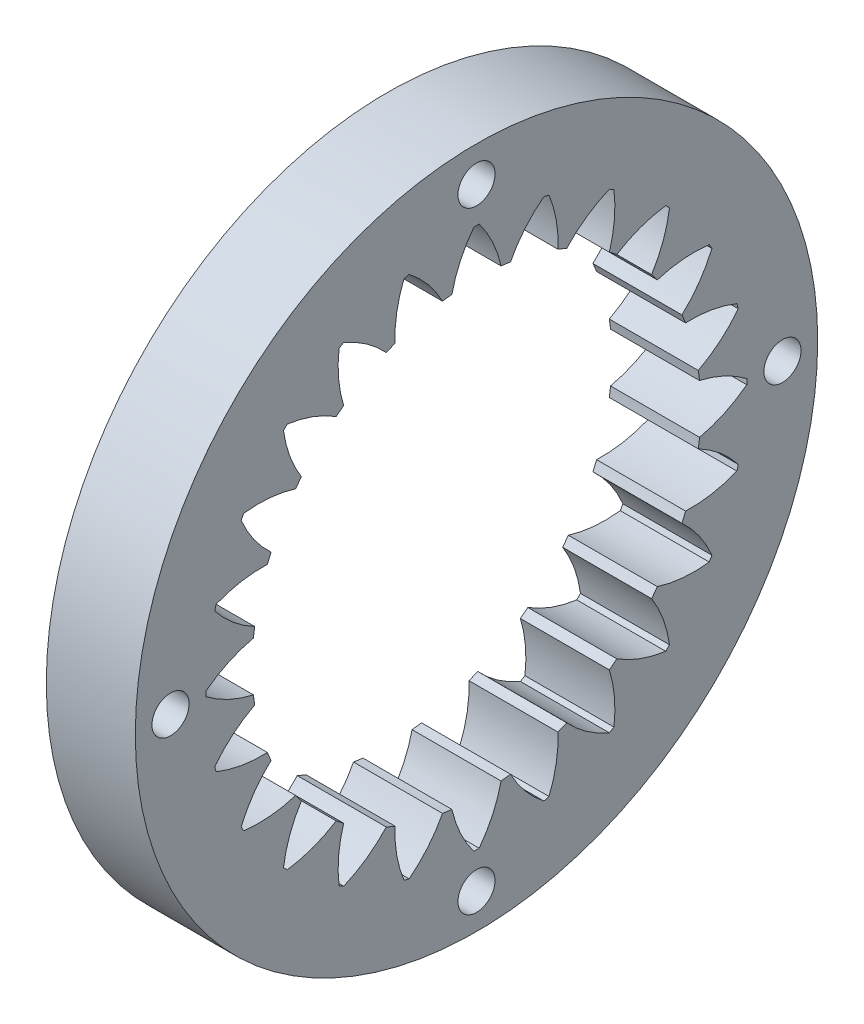
SolidWorks part; units mm, degrees
ref_plane "Plane1" through (0, 0, 0) normal (0, 0, 1) x (1, 0, 0)
ref_plane "Plane2" through (0, 0, 0) normal (0, 1, 0) x (1, 0, 0)
ref_plane "Plane3" through (0, 0, 0) normal (1, 0, 0) x (0, 0, -1)
sketch "HoldingSke" plane through (0, 0, 0) normal (0, 1, 0) x (1, 0, 0)
  line L0 (0, 0) -> (0.3322, -0.1479)
  line L1 (-15, 0) -> (100, 0) construction
  line L2 (0, 0) -> (-2.1039, 2.3779)
  line L3 (0, 0) -> (-11.863, 4.5341)
  line L4 (0, 0) -> (7.8894, 3.5126)
  line L5 (0, 0) -> (-23.7986, -8.8762)
  line L6 (0, 0) -> (-10.5278, -7.1032)
  line L7 (-2.1039, 2.3779) -> (3.3635, 27.1825)
  line L8 (-76.2, 5.1279) -> (-54.61, 5.1279)
  line L9 (-71.009, 38.7566) -> (-53.1078, 45.2721)
  line L10 (-76.2, 71.12) -> (104.1128, 71.12)
  line L11 (0, 0) -> (-12, 0)
  line L12 (-76.2, 101.6) -> (-76.103, 101.6)
  line L13 (24.9733, 27.94) -> (52.9518, 28.4284)
  line L14 (24.9733, 27.94) -> (24.9743, 27.94)
  line L15 (24.9733, 27.94) -> (100.4006, 29.5858)
  circle A0 centre (0, 0) radius 12.5
  circle A1 centre (0, 0) radius 12.7
  circle A2 centre (0, 0) radius 12.7
  dimension "MHD" = 25.4
  dimension "Hub_dia" = 25.4
  dimension "Diameter" = 25
  dimension "Num_teeth" = 24
  dimension "Pitch" = 0.3636
  dimension "Overall_len" = 25.4
  dimension "Show_teeth" = 24
  dimension "Thickness" = 12.7
  dimension "OAL" = 25.4001
  dimension "T_dim" = 21.59
  dimension "Ap" = 20
  dimension "H" = 19.05
  dimension "Pitch_radius" = 180.3128
  dimension "Width" = 12
  dimension "Backlash" = 0.097
  dimension "Addendum_fac" = 1
  dimension "Dedendum_fac" = 1.25
  dimension "Clearance_fac" = 0.25
  dimension "Dedendum_add" = 0.001
  dimension "Module" = 2.75
sketch "BasProSke" plane through (0, 0, 0) normal (0, 1, 0) x (1, 0, 0)
  line L0 (-10, 0) -> (60, 0) construction
  line L1 (0, 30.25) -> (0, 36.4639)
  line L2 (0, 30.25) -> (12, 30.25)
  line L3 (12, 30.25) -> (12, 36.4639)
  line L4 (12, 36.4639) -> (0, 36.4639)
  dimension "Thickness" = 12
  dimension "Diameter" = 72.9278
  dimension "Inside_diameter" = 60.5
revolve "Base-Revolve" add sketch "BasProSke" angle 360 about L0
sketch "TooCutSke" plane through (0, 0, 0) normal (1, 0, 0) x (0, 0, -1)
  line L3 (2.4008, 32.9126) -> (2.4008, 53.6633) construction
  line L4 (0, 0) -> (0, 59.563) construction
  line L5 (0, 0) -> (-8.9185, 67.7429) construction
  line L6 (-12.7878, 26.4661) -> (33.8762, 32.6096) construction
  circle A0 centre (0, 0) radius 33 construction
  circle A1 centre (0, 0) radius 36.4385 construction
  circle A2 centre (0, 0) radius 27.9089 construction
  circle A3 centre (0, 0) radius 30.2246 construction
  arc A4 (3.3201, 30.0417) -> (0.359, 36.4367) centre (-12.7878, 26.4661) ccw
  arc A5 (3.3201, 30.0417) -> (-3.3201, 30.0417) centre (0, 0) ccw
  arc A6 (0.359, 36.4367) -> (-0.359, 36.4367) centre (0, 0) ccw
  arc A7 (-0.359, 36.4367) -> (-3.3201, 30.0417) centre (12.7878, 26.4661) ccw
  dimension "Pitch_dia" = 66
  dimension "Base_dia" = 55.8177
  dimension "Root_dia" = 72.877
  dimension "Overcut_dia" = 60.4492
  dimension "Flank_rad" = 16.5
  dimension "Half_ang" = 7.5
  dimension "Half_CT" = 2.4008
extrude "ToothCut" cut sketch "TooCutSke" along normal through all
fillet "Breaks" [suppressed] radius 0.275
fillet "RootFillets" [suppressed] radius 0.6885
pattern_circular "TeethCuts" count 24 every 15 about axis through (-10, 0, 0) along (1, 0, 0) of "RootFillets", "Breaks", "ToothCut"
sketch "Sketch1" plane through (12, 0, 0) normal (1, 0, 0) x (0, 0, -1)
  circle A0 centre (0, 0) radius 36.4385
  circle A1 centre (0, 0) radius 46
  dimension "D1" = 72.877
  dimension "D2" = 92
extrude "Boss-Extrude1" add sketch "Sketch1" against normal blind 12
sketch "Sketch2" plane through (12, 0, 0) normal (1, 0, 0) x (0, 0, -1)
  circle A0 centre (41.25, 0) radius 2.5
  circle A1 centre (0, -41.25) radius 2.5
  circle A2 centre (-41.25, 0) radius 2.5
  circle A3 centre (0, 41.25) radius 2.5
  point P12 (0, 0)
  dimension "D1" = 5
  dimension "D2" = 41.25
  dimension "D3" = 4
extrude "Cut-Extrude1" cut sketch "Sketch2" against normal blind 12
equation "' \"Module@HoldingSke\" = 6.35"
equation "' \"Num_teeth@HoldingSke\" = 24"
equation "' \"Ap@HoldingSke\" =  14.5"
equation "' \"Ap@HoldingSke\" = 14.5"
equation "' \"Width@HoldingSke\" = 12"
equation "' \"Diameter@HoldingSke\" = 8 * 25.4"
equation "' \"Show_teeth@HoldingSke\" = 100"
equation "' \"Backlash@HoldingSke\" = 0.009 * 25.4"
equation "' \"Addendum_fac@HoldingSke\" = 1.0"
equation "' \"Dedendum_fac@HoldingSke\" = 1.25"
equation "' \"Dedendum_add@HoldingSke\" = 0.00005 * 25.4"
equation "' \"Clearance_fac@HoldingSke\" = 0.25"
equation "\"Pitch@HoldingSke\" = 1 / \"Module@HoldingSke\" "
equation "\"Overcut_dia@TooCutSke\" = (\"Num_teeth@HoldingSke\" - 2 * \"Addendum_fac@HoldingSke\") / \"Pitch@HoldingSke\" - 0.002 * 25.4"
equation "\"Pitch_dia@TooCutSke\" = \"Num_teeth@HoldingSke\" / \"Pitch@HoldingSke\""
equation "\"Base_dia@TooCutSke\" = \"Num_teeth@HoldingSke\" / \"Pitch@HoldingSke\" * cos((\"Ap@HoldingSke\"  * 3.14159265 / 180)) * 0.90"
equation "\"Root_dia@TooCutSke\" = \"Num_teeth@HoldingSke\"  / \"Pitch@HoldingSke\" + 2 *  \"Dedendum_fac@HoldingSke\"/ \"Pitch@HoldingSke\" + \"Dedendum_add@HoldingSke\" * 2"
equation "\"Half_ang@TooCutSke\" = 180 / \"Num_teeth@HoldingSke\""
equation "\"Half_CT@TooCutSke\" = \"Num_teeth@HoldingSke\" / \"Pitch@HoldingSke\" * sin((3.14159265 / 2 / \"Num_teeth@HoldingSke\")) / 2 + 10 * \"Backlash@HoldingSke\" / 4"
equation "\"Flank_rad@TooCutSke\" = \"Num_teeth@HoldingSke\" / \"Pitch@HoldingSke\" / 4"
equation "\"Radius@RootFillets\"= \"Clearance_fac@HoldingSke\" / \"Pitch@HoldingSke\" + \"Dedendum_add@HoldingSke\""
equation "\"Break_rad@Breaks\" = 0.02 / \"Pitch@HoldingSke\" * 5"
equation "\"Num_teeth@TeethCuts\" = int( \"Show_teeth@HoldingSke\" ) + 1"
equation "\"Num_teeth@TeethCuts\" = ((sgn( \"Num_teeth@TeethCuts\" - \"Num_teeth@HoldingSke\" )-1)*( \"Num_teeth@TeethCuts\" - \"Num_teeth@HoldingSke\" ))/-2+ \"Num_teeth@HoldingSke\""
equation "\"Num_teeth@TeethCuts\" = ((sgn( \"Num_teeth@TeethCuts\" - 2.0)+1)*( \"Num_teeth@TeethCuts\" - 2.0))/2 +2.0"
equation "\"Angle@TeethCuts\" = 360.0 / \"Num_teeth@HoldingSke\""
equation "\"Diameter@BasProSke\" = \"Num_teeth@HoldingSke\"  / \"Pitch@HoldingSke\" + 2 *  \"Dedendum_fac@HoldingSke\"/ \"Pitch@HoldingSke\" + \"Dedendum_add@HoldingSke\" * 2 + 0.002 * 25.4"
equation "\"Diameter@BasProSke\" = ((sgn( \"Diameter@BasProSke\"  - \"Diameter@HoldingSke\" )+1)*( \"Diameter@BasProSke\"  - \"Diameter@HoldingSke\" ))/2 + \"Diameter@HoldingSke\""
equation "\"Inside_diameter@BasProSke\" =  (\"Num_teeth@HoldingSke\" - 2 * \"Addendum_fac@HoldingSke\") / \"Pitch@HoldingSke\" "
equation "\"Thickness@BasProSke\"  = \"Width@HoldingSke\""
